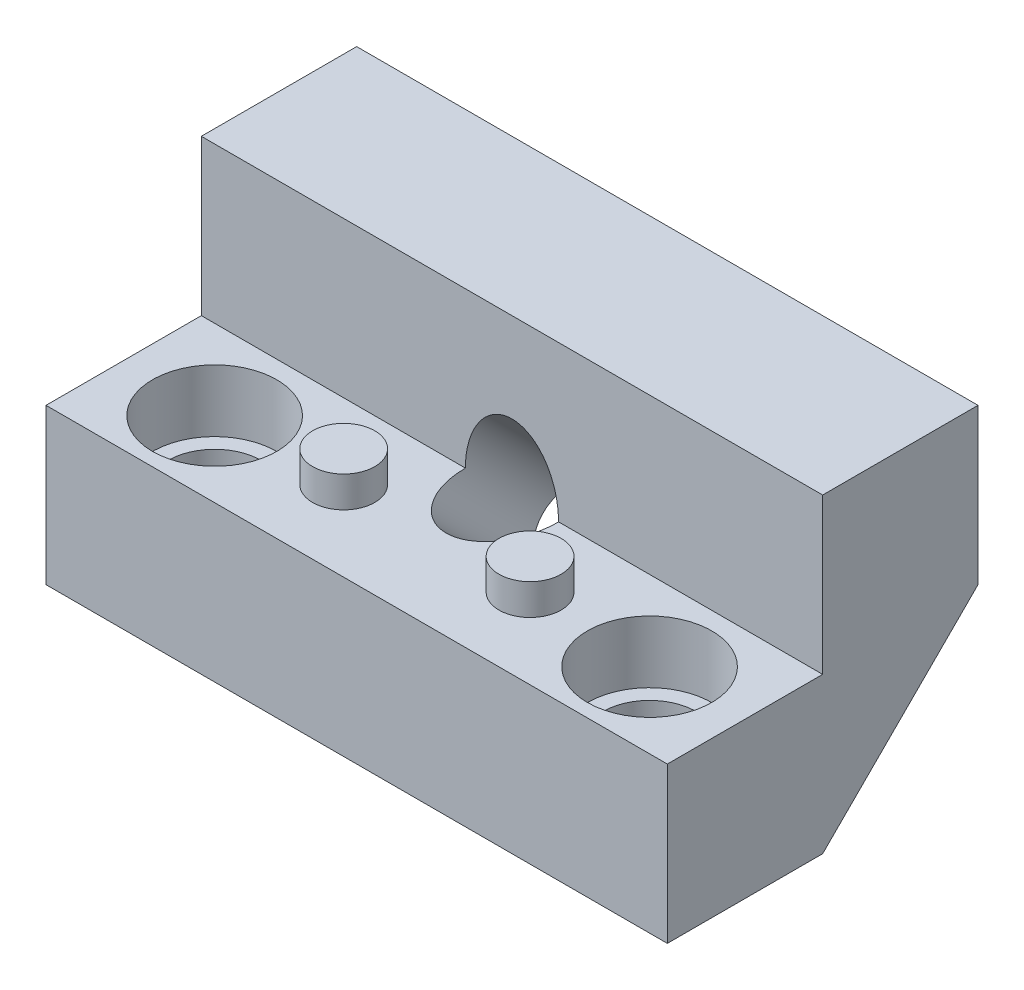
SolidWorks part; units mm, degrees
ref_plane "Front Plane" through (0, 0, 0) normal (0, 0, 1) x (1, 0, 0)
ref_plane "Top Plane" through (0, 0, 0) normal (0, 1, 0) x (1, 0, 0)
ref_plane "Right Plane" through (0, 0, 0) normal (1, 0, 0) x (0, 0, -1)
sketch "Sketch1" plane through (0, 0, 0) normal (0, 1, 0) x (1, 0, 0)
  line L1 (-127, -63.5) -> (127, -63.5)
  line L2 (-127, -63.5) -> (-127, 63.5)
  line L3 (-127, 63.5) -> (127, 63.5)
  line L4 (127, -63.5) -> (127, 63.5)
  line L5 (-127, -63.5) -> (127, 63.5) construction
  line L6 (-127, 63.5) -> (127, -63.5) construction
  point P0 (0, 0)
  dimension "D1" = 254
  dimension "D2" = 127
extrude "Rectangle prison" add sketch "Sketch1" along normal blind 127 contours L2 L1 L4 L3
sketch "Sketch6" plane through (127, 0, 0) normal (1, 0, 0) x (0, 0, -1)
  line L0 (-63.5, 63.5) -> (0, 63.5)
  line L1 (-63.5, 127) -> (-63.5, 0) construction
  line L2 (0, 63.5) -> (0, 127)
  line L3 (-63.5, 127) -> (63.5, 127) construction
extrude "Top square cut" cut sketch "Sketch6" against normal through all and the other way through all
sketch "Sketch7" plane through (127, 0, 0) normal (1, 0, 0) x (0, 0, -1)
  line L0 (0, 0) -> (63.5, 63.5)
  line L1 (63.5, 127) -> (63.5, 0) construction
extrude "Buttom tri cut" cut sketch "Sketch7" against normal through all and the other way through all flip side to cut
sketch "Sketch8" plane through (0, 63.5, 0) normal (0, 1, 0) x (1, 0, 0)
  circle A0 centre (-88.9, -32.6581) radius 25.4
  circle A1 centre (88.9, -32.6581) radius 25.4
  point P6 (90.5324, -30.9138)
  point P7 (91.8891, -32.6581)
extrude "outer circle cut" cut sketch "Sketch8" against normal blind 25.4
sketch "Sketch9" plane through (0, 38.1, 0) normal (0, 1, 0) x (1, 0, 0)
  circle A0 centre (-88.9, -32.6581) radius 19.05
  circle A1 centre (88.9, -32.6581) radius 19.05
  dimension "D1" = 38.1
  dimension "D2" = 38.1
extrude "inner circle cut" cut sketch "Sketch9" against normal through all contours A0 | A1
sketch "Sketch11" plane through (0, 63.5, 0) normal (0, 1, 0) x (1, 0, 0)
  circle A0 centre (-38.1, -30.7102) radius 12.7
  circle A1 centre (38.1, -30.7102) radius 12.7
  point P5 (38.1, -30.7102)
  dimension "D1" = 25.4
  dimension "D2" = 38.1
  dimension "D3" = 38.1
extrude "Two circles out" add sketch "Sketch11" along normal blind 12.7
sketch "Sketch12" plane through (0, 0, 0) normal (0, -0.7071, -0.7071) x (1, 0, 0)
  line L1 (-127, -44.9013) -> (127, -44.9013) construction
  line L2 (127, 0) -> (127, -89.8026) construction
  circle A0 centre (0, -44.9013) radius 19.05
  dimension "D1" = 38.1
extrude "Circle cut in the middle" cut sketch "Sketch12" against normal through all
